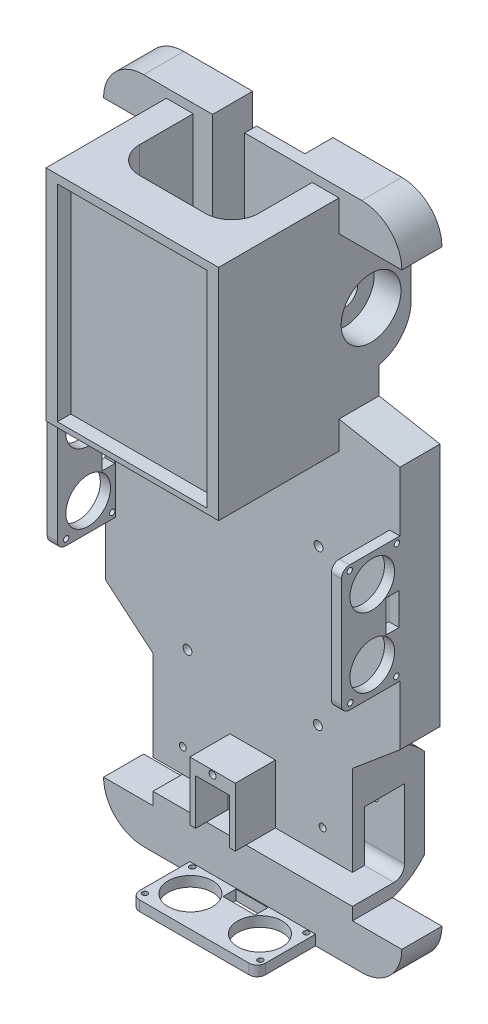
SolidWorks part; units mm, degrees
ref_plane "Alzado" through (0, 0, 0) normal (0, 0, 1) x (1, 0, 0)
ref_plane "Planta" through (0, 0, 0) normal (0, 1, 0) x (1, 0, 0)
ref_plane "Vista lateral" through (0, 0, 0) normal (1, 0, 0) x (0, 0, -1)
sketch "Croquis1" plane through (0, 0, 0) normal (0, 0, 1) x (1, 0, 0)
  line L0 (-55.75, 30) -> (-32.25, 30)
  line L1 (-32.25, 30) -> (-32.25, -30)
  line L2 (-32.25, -30) -> (-55, -34.2202)
  line L3 (-55, -34.2202) -> (-55, -125.7202)
  line L4 (-40.7501, 45) -> (0, 45)
  line L6 (-15, 15) -> (-15, -15)
  line L11 (-55, -125.7202) -> (-37.2737, -140.5944)
  line L12 (40.75, 45) -> (0, 45)
  line L17 (55, -125.7202) -> (37.2737, -140.5944)
  line L20 (15, 15) -> (15, -15)
  line L21 (-55, -79.9702) -> (55, -79.9702) construction
  line L22 (55, -34.2202) -> (55, -125.7202)
  line L23 (32.25, -30) -> (55, -34.2202)
  line L24 (32.25, 30) -> (32.25, -30)
  line L25 (55.75, 30) -> (32.25, 30)
  line L26 (-55.75, -189.9405) -> (-37.2737, -189.9405)
  line L27 (55.75, -189.9405) -> (37.2737, -189.9405)
  line L28 (40.75, -204.9405) -> (0, -204.9405)
  line L29 (-40.7501, -204.9405) -> (0, -204.9405)
  line L30 (-37.2737, -189.9405) -> (-37.2737, -140.5944)
  line L31 (37.2737, -189.9405) -> (37.2737, -140.5944)
  line L32 (-15, 15) -> (15, 15)
  line L33 (-15, -15) -> (15, -15)
  arc A4 (-55.75, 30) -> (-40.7501, 45) centre (-40.75, 30) cw
  arc A5 (55.75, 30) -> (40.75, 45) centre (40.75, 30) ccw
  arc A8 (55.75, -189.9405) -> (40.75, -204.9405) centre (40.75, -189.9405) cw
  arc A9 (-55.75, -189.9405) -> (-40.7501, -204.9405) centre (-40.75, -189.9405) ccw
  point P11 (0, 15)
  point P13 (-15, 0)
  point P20 (-32.25, 0)
  dimension "D10" = 15
  dimension "D22" = 15
  dimension "D1" = 60
  dimension "D3" = 55
  dimension "D4" = 23.5
  dimension "D5" = 91.5
  dimension "D6" = 23.1381
  dimension "D7" = 30
  dimension "D8" = 30
  dimension "D9" = 17.25
  dimension "D11" = 14.9999
  dimension "D12" = 15
  dimension "D13" = 23.14
  dimension "D14" = 18.4763
  dimension "D16" = 130
  dimension "D19" = 15
  dimension "D20" = 110
  dimension "D21" = 23.14
  dimension "D23" = 23.5
  dimension "D24" = 23.1381
extrude "Saliente-Extruir1" add sketch "Croquis1" along normal blind 15
sketch "Croquis6" plane through (-32.25, 0, 0) normal (-1, 0, 0) x (0, 0, 1)
  line L5 (0, 0) -> (5.215, 0) construction
  line L6 (0, 30) -> (0, -30) construction
  circle A0 centre (3, 0) radius 11.175
  circle A1 centre (3, 0) radius 5 construction
  circle A2 centre (3, 0) radius 25 construction
  dimension "D1" = 22.35
  dimension "D3" = 10
  dimension "D4" = 50
  dimension "D2" = 3
extrude "Cortar-Extruir1" cut sketch "Croquis6" against normal blind 10
sketch "Croquis11" plane through (0, 0, 0) normal (0, 0, -1) x (-1, 0, 0)
  line L0 (32.25, -10.7648) -> (32.25, -30) construction
  line L1 (15, 20) -> (32.25, 20)
  line L2 (15, 20) -> (15, -20)
  line L3 (15, -20) -> (32.25, -20)
  line L4 (32.25, 20) -> (32.25, -20)
  line L5 (15, 15) -> (15, -15) construction
  line L6 (55.75, 30) -> (32.25, 30) construction
  line L7 (0, -8.0419) -> (0, 11.3864) construction
  line L8 (-15, -20) -> (-32.25, -20)
  line L9 (-32.25, 20) -> (-32.25, -20)
  line L10 (-15, 20) -> (-32.25, 20)
  line L11 (-15, 20) -> (-15, -20)
  dimension "D1" = 10
  dimension "D2" = 10
extrude "Saliente-Extruir3" add sketch "Croquis11" along normal blind 12
sketch "Croquis9" plane through (-22.25, 0, 0) normal (-1, 0, 0) x (0, 0, 1)
  circle A0 centre (3, 0) radius 5
  arc A1 (0, -10.7648) -> (0, 10.7648) centre (3, 0) ccw construction
  dimension "D1" = 10
extrude "Cortar-Extruir2" cut sketch "Croquis9" against normal through all both and the other way through all
sketch "Croquis12" plane through (32.25, 0, 0) normal (1, 0, 0) x (0, 0, -1)
  line L2 (0, 0) -> (-9.4705, 0) construction
  line L5 (12, 20) -> (12, -20) construction
  line L6 (0, 20) -> (12, 20)
  line L7 (12, 20) -> (12, 5)
  line L8 (12, -20) -> (12, -5)
  line L9 (0, -20) -> (12, -20)
  arc A3 (12, 5) -> (0, 20) centre (-3.375, 5) ccw
  arc A4 (12, -5) -> (0, -20) centre (-3.375, -5) cw
  dimension "D1" = 15
sketch "Croquis14" plane through (0, 0, 15) normal (0, 0, 1) x (1, 0, 0)
  line L0 (-32.25, 30) -> (-32.25, -30) construction
  line L1 (32.25, 41.5932) -> (-32.25, 41.5932)
  line L2 (32.25, 41.5932) -> (32.25, -40.4068)
  line L3 (32.25, -40.4068) -> (-32.25, -40.4068)
  line L4 (-32.25, 41.5932) -> (-32.25, -40.4068)
  line L5 (32.25, -30) -> (32.25, 30) construction
  line L8 (40.75, 45) -> (-40.7501, 45) construction
  dimension "D1" = 3.4068
  dimension "D2" = 10.4068
extrude "Saliente-Extruir4" add sketch "Croquis14" along normal blind 40
sketch "Croquis10" plane through (32.25, 0, 0) normal (1, 0, 0) x (0, 0, -1)
  circle A0 centre (-3, 0) radius 11.175
  circle A1 centre (-3, 0) radius 5 construction
  arc A2 (0, 10.7648) -> (0, -10.7648) centre (-3, 0) ccw construction
extrude "Cortar-Extruir3" cut sketch "Croquis10" against normal blind 10
sketch "Croquis13" plane through (-32.25, 0, 0) normal (-1, 0, 0) x (0, 0, 1)
  circle A0 centre (3, 0) radius 11.175
  arc A1 (0, -10.7648) -> (0, 10.7648) centre (3, 0) ccw construction
extrude "Cortar-Extruir5" cut sketch "Croquis13" against normal blind 10 and the other way through all
sketch "Croquis15" plane through (0, -40.4068, 0) normal (0, -1, 0) x (1, 0, 0)
  line L0 (-22.25, 15) -> (-22.25, 35)
  line L1 (-32.25, 15) -> (32.25, 15) construction
  line L2 (-12.25, 45) -> (12.25, 45)
  line L3 (22.25, 35) -> (22.25, 15)
  line L4 (22.25, 15) -> (-22.25, 15)
  line L5 (-32.25, 55) -> (-32.25, 15) construction
  line L6 (32.25, 55) -> (32.25, 15) construction
  line L7 (-32.25, 55) -> (32.25, 55) construction
  arc A0 (22.25, 35) -> (12.25, 45) centre (12.25, 35) ccw
  arc A1 (-22.25, 35) -> (-12.25, 45) centre (-12.25, 35) cw
  dimension "D4" = 10
  dimension "D1" = 10
  dimension "D2" = 10
  dimension "D3" = 10
extrude "Cortar-Extruir6" cut sketch "Croquis15" against normal through all
sketch "Croquis16" plane through (0, 0, 55) normal (0, 0, 1) x (1, 0, 0)
  line L1 (-28, 38.5) -> (28, 38.5)
  line L2 (-28, 38.5) -> (-28, -38.5)
  line L3 (-28, -38.5) -> (28, -38.5)
  line L4 (28, 38.5) -> (28, -38.5)
  line L5 (-32.25, 41.5932) -> (32.25, 41.5932)
  line L6 (-32.25, 41.5932) -> (-32.25, -40.4068)
  line L7 (-32.25, -40.4068) -> (32.25, -40.4068)
  line L8 (32.25, 41.5932) -> (32.25, -40.4068)
  point P4 (0, 38.5)
  point P6 (28, 0)
  dimension "D1" = 77
  dimension "D2" = 56
extrude "Saliente-Extruir5" add sketch "Croquis16" along normal blind 5
sketch "Croquis17" plane through (0, 0, 15) normal (0, 0, 1) x (1, 0, 0)
  line L0 (15, 15) -> (15, 45)
  line L1 (15, 45) -> (-15, 45)
  line L2 (40.75, 45) -> (-40.7501, 45) construction
  line L3 (-15, 45) -> (-15, 15)
  line L4 (15, 15) -> (-15, 15) construction
  line L5 (15, 15) -> (-15, 15)
  line L6 (-15, 15) -> (-15, -15) construction
extrude "Cortar-Extruir7" cut sketch "Croquis17" against normal through all
sketch "Croquis19" plane through (0, -15, 0) normal (0, 1, 0) x (1, 0, 0)
  line L0 (-15, -15) -> (-15, 0) construction
  line L1 (15, -15) -> (-3, -15)
  line L2 (15, -15) -> (15, -10.5)
  line L3 (15, -10.5) -> (-3, -10.5)
  line L4 (-3, -15) -> (-3, -10.5)
  dimension "D1" = 12
  dimension "D2" = 2.5
extrude "Saliente-Extruir6" add sketch "Croquis19" along normal up to vertex (60 mm away)
sketch "Croquis22" plane through (0, -15, 0) normal (0, 1, 0) x (1, 0, 0)
  line L1 (-15, 0) -> (-3, 0)
  line L2 (-15, 0) -> (-15, -15)
  line L3 (-15, -15) -> (-3, -15)
  line L4 (-3, 0) -> (-3, -15)
extrude "Cortar-Extruir8" cut sketch "Croquis22" against normal blind 2
sketch "Croquis23" plane through (0, 0, 15) normal (0, 0, 1) x (1, 0, 0)
  line L1 (51.2, -56.4702) -> (55, -56.4702)
  line L2 (51.2, -56.4702) -> (51.2, -103.4702)
  line L3 (51.2, -103.4702) -> (55, -103.4702)
  line L4 (55, -56.4702) -> (55, -103.4702)
  line L6 (55, -125.7202) -> (55, -34.2202) construction
  line L7 (0, 0) -> (0, -130.3454) construction
  line L8 (-51.2, -103.4702) -> (-55, -103.4702)
  line L9 (-55, -56.4702) -> (-55, -103.4702)
  line L10 (-51.2, -56.4702) -> (-55, -56.4702)
  line L11 (-51.2, -56.4702) -> (-51.2, -103.4702)
  point P6 (55, -79.9702)
  point P7 (55, -79.9702)
  dimension "D1" = 3.8
  dimension "D2" = 47
extrude "Saliente-Extruir8" add sketch "Croquis23" along normal blind 19.8
sketch "Croquis24" plane through (55, 0, 0) normal (1, 0, 0) x (0, 0, -1)
  line L0 (-34.8, -103.4702) -> (-15, -103.4702) construction
  line L1 (-34.8, -103.4702) -> (-34.8, -56.4702) construction
  line L2 (-34.8, -102.4702) -> (-15, -102.4702) construction
  line L3 (-34.8, -102.4702) -> (-34.8, -57.4702) construction
  line L4 (-34.8, -57.4702) -> (-15, -57.4702) construction
  line L5 (-15, -102.4702) -> (-15, -57.4702) construction
  line L6 (-15, -125.7202) -> (-15, -103.4702) construction
  line L7 (-34.8, -56.4702) -> (-15, -56.4702) construction
  line L8 (-20.1, -85.9702) -> (-15.3, -85.9702)
  line L9 (-20.1, -85.9702) -> (-20.1, -73.9702)
  line L10 (-20.1, -73.9702) -> (-15.3, -73.9702)
  line L11 (-15.3, -85.9702) -> (-15.3, -73.9702)
  line L12 (-24.9, -56.4702) -> (-24.9, -58.3702) construction
  line L13 (-24.9, -103.4702) -> (-24.9, -101.771) construction
  circle A0 centre (-25.3, -66.9702) radius 8.35
  circle A1 centre (-25.3, -92.9702) radius 8.35
  circle A2 centre (-16.3, -101.2702) radius 1
  circle A3 centre (-33.7, -58.3702) radius 1
  circle A4 centre (-16.1, -58.3702) radius 1
  circle A5 centre (-33.5, -101.2702) radius 1
  point P16 (-20.1, -79.9702)
  point P20 (-34.8, -79.9702)
  point P21 (-34.8, -79.9702)
  dimension "D1" = 16.7
  dimension "D2" = 16.7
  dimension "D3" = 2
  dimension "D4" = 2.2
  dimension "D5" = 2
  dimension "D6" = 1.9
  dimension "D7" = 45
  dimension "D8" = 13
  dimension "D9" = 1.3
  dimension "D10" = 1.1
  dimension "D11" = 13
  dimension "D12" = 12
  dimension "D13" = 4.8
  dimension "D14" = 0.3
  dimension "D15" = 9.5
extrude "Cortar-Extruir10" cut sketch "Croquis24" against normal through all
sketch "Croquis25" plane through (0, 0, 34.8) normal (0, 0, 1) x (1, 0, 0)
  line L1 (-55, -56.4702) -> (-51.2, -56.4702)
  line L2 (-55, -56.4702) -> (-55, -103.4702)
  line L3 (-55, -103.4702) -> (-51.2, -103.4702)
  line L4 (-51.2, -56.4702) -> (-51.2, -103.4702)
  line L5 (51.2, -56.4702) -> (55, -56.4702)
  line L6 (51.2, -56.4702) -> (51.2, -103.4702)
  line L7 (51.2, -103.4702) -> (55, -103.4702)
  line L8 (55, -56.4702) -> (55, -103.4702)
extrude "Saliente-Extruir9" add sketch "Croquis25" along normal blind 2
fillet "Redondeo2" radius 3 4 edges at (53.1, -56.4702, 36.8) (53.1, -103.4702, 36.8) (-53.1, -56.4702, 36.8) (-53.1, -103.4702, 36.8)
sketch "Croquis26" plane through (0, 0, 15) normal (0, 0, 1) x (1, 0, 0)
  line L0 (-23.5001, -201.1405) -> (-23.5001, -204.9405)
  line L1 (-23.5001, -204.9405) -> (23.4999, -204.9405)
  line L2 (23.4999, -204.9405) -> (23.4999, -201.1405)
  line L3 (23.4999, -201.1405) -> (-23.5001, -201.1405)
  line L4 (-40.7501, -204.9405) -> (40.75, -204.9405) construction
  point P6 (-0.0001, -204.9405)
  point P7 (-0.0001, -204.9405)
  dimension "D1" = 3.8
  dimension "D2" = 47
extrude "Saliente-Extruir10" add sketch "Croquis26" along normal blind 21.8
fillet "Redondeo3" radius 3 2 edges at (23.4999, -203.0405, 36.8) (-23.5001, -203.0405, 36.8)
sketch "Croquis28" plane through (0, -204.9405, 0) normal (0, -1, 0) x (1, 0, 0)
  line L0 (-32.25, 15) -> (-22.25, 15) construction
  line L1 (-6, 20.1) -> (6, 20.1)
  line L2 (-6, 20.1) -> (-6, 15.3)
  line L3 (-6, 15.3) -> (6, 15.3)
  line L4 (6, 20.1) -> (6, 15.3)
  line L5 (-20.5001, 36.8) -> (20.4999, 36.8) construction
  line L6 (-23.5001, 33.8) -> (-23.5001, 15) construction
  line L8 (23.4999, 33.8) -> (23.4999, 15) construction
  line L9 (0, -0.6164) -> (0, 0) construction
  line L10 (0, 0) -> (0, -5.7529) construction
  circle A0 centre (-13, 25.3) radius 8.35
  circle A1 centre (13, 25.3) radius 8.35
  circle A2 centre (-21.3001, 16.3) radius 1
  circle A3 centre (21.5999, 33.7) radius 1
  circle A4 centre (21.3001, 16.3) radius 1
  circle A5 centre (-21.5999, 33.7) radius 1
  point P6 (0, 15.3)
  dimension "D4" = 16.7
  dimension "D7" = 16.7
  dimension "D9" = 2
  dimension "D12" = 2
  dimension "D1" = 0.3
  dimension "D2" = 12
  dimension "D3" = 4.8
  dimension "D5" = 13
  dimension "D6" = 13
  dimension "D8" = 11.5
  dimension "D10" = 2.2
  dimension "D11" = 1.3
  dimension "D13" = 1.9
  dimension "D14" = 3.1
extrude "Cortar-Extruir11" cut sketch "Croquis28" against normal blind 21.8
extrude "Cortar-Extruir12" cut sketch "Croquis12" against normal through all both and the other way through all
sketch "Croquis29" plane through (0, 0, 15) normal (0, 0, 1) x (1, 0, 0)
  line L2 (0, 0) -> (0, -45.8702) construction
  circle A0 centre (-24.3737, -132.9944) radius 1.65
  circle A1 centre (24.6263, -74.9944) radius 1.65
  circle A2 centre (-24.6263, -74.9944) radius 1.65
  circle A3 centre (24.3737, -132.9944) radius 1.65
  dimension "D1" = 3.3
  dimension "D3" = 12.9
  dimension "D4" = 3.3
  dimension "D2" = 7.6
  dimension "D5" = 58
  dimension "D6" = 49
extrude "Cortar-Extruir13" cut sketch "Croquis29" against normal through all both and the other way through all
sketch "Croquis32" plane through (0, 0, 0) normal (0, 0, -1) x (-1, 0, 0)
  line L0 (0, 0) -> (0, -47.6418) construction
  circle A0 centre (-24.6263, -74.9944) radius 5.15
  circle A1 centre (-24.6263, -74.9944) radius 1.65 construction
  circle A2 centre (-24.3737, -132.9944) radius 5.15
  circle A3 centre (-24.3737, -132.9944) radius 1.65 construction
  circle A4 centre (24.3737, -132.9944) radius 5.15
  circle A5 centre (24.6263, -74.9944) radius 5.15
  dimension "D1" = 3.5
  dimension "D2" = 3.5
extrude "Cortar-Extruir14" cut sketch "Croquis32" against normal blind 8 and the other way through all
sketch "Croquis34" plane through (0, 0, 0) normal (0, 0, -1) x (-1, 0, 0)
  line L0 (-37.2737, -189.9405) -> (-37.2737, -140.5944) construction
  line L1 (-37.2737, -140.5944) -> (-15, -140.5944)
  line L2 (-37.2737, -140.5944) -> (-37.2737, -189.9405)
  line L3 (-37.2737, -189.9405) -> (-15, -189.9405)
  line L4 (-15, -140.5944) -> (-15, -189.9405)
  line L5 (-15, 45) -> (-15, 20) construction
  line L6 (15, -140.5944) -> (37.2737, -140.5944)
  line L7 (15, -140.5944) -> (15, -189.9405)
  line L8 (15, -189.9405) -> (37.2737, -189.9405)
  line L9 (37.2737, -140.5944) -> (37.2737, -189.9405)
  line L10 (37.2737, -140.5944) -> (37.2737, -189.9405) construction
  line L11 (15, 20) -> (15, 45) construction
extrude "Saliente-Extruir11" add sketch "Croquis34" along normal blind 12
sketch "Croquis35" plane through (37.2737, 0, 0) normal (1, 0, 0) x (0, 0, -1)
  line L0 (0, -140.5944) -> (12, -140.5944)
  line L1 (12, -140.5944) -> (12, -148.5944)
  line L3 (0, -189.9405) -> (12, -189.9405)
  line L4 (12, -189.9405) -> (12, -181.9405)
  line L5 (12, -140.5944) -> (12, -189.9405) construction
  arc A3 (0, -189.9405) -> (12, -181.9405) centre (-7.782, -165.2674) ccw
  arc A4 (12, -148.5944) -> (0, -140.5944) centre (-7.782, -165.2674) ccw
  dimension "D1" = 8
extrude "Cortar-Extruir17" cut sketch "Croquis35" against normal through all both and the other way through all
sketch "Croquis37" plane through (-37.2737, 0, 0) normal (-1, 0, 0) x (0, 0, 1)
  line L0 (-12, -181.9405) -> (-12, -148.5944) construction
  line L1 (0, -140.5944) -> (0, -189.9405) construction
  line L7 (-4.5, -155.2674) -> (10.5, -155.2674)
  line L8 (-4.5, -155.2674) -> (-4.5, -181.2674)
  line L9 (-0.5, -185.2674) -> (6.5, -185.2674)
  line L10 (10.5, -155.2674) -> (10.5, -181.2674)
  circle A0 centre (3, -165.2674) radius 5.5 construction
  arc A1 (6.5, -185.2674) -> (10.5, -181.2674) centre (6.5, -181.2674) ccw
  arc A2 (-0.5, -185.2674) -> (-4.5, -181.2674) centre (-0.5, -181.2674) cw
  point P5 (-12, -165.2674)
  point P14 (3, -185.2674)
  point P16 (10.5, -185.2674)
  point P19 (-4.5, -185.2674)
  dimension "D1" = 11
  dimension "D4" = 30
  dimension "D6" = 4
  dimension "D2" = 3
  dimension "D3" = 10
  dimension "D5" = 15
extrude "Cortar-Extruir18" cut sketch "Croquis37" against normal through all both and the other way through all
sketch "Croquis38" plane through (0, 0, -12) normal (0, 0, -1) x (-1, 0, 0)
  line L0 (-37.2737, -148.5944) -> (-37.2737, -181.9405) construction
  line L1 (-15, -148.5944) -> (-37.2737, -148.5944) construction
  line L2 (0, 0) -> (0, -210.3255) construction
  circle A0 centre (-26.1369, -165.2674) radius 1.3
  circle A1 centre (26.1369, -165.2674) radius 1.3
  point P5 (-37.2737, -165.2674)
  point P9 (-26.1369, -148.5944)
  dimension "D1" = 2.6
extrude "Cortar-Extruir19" cut sketch "Croquis38" against normal through all both and the other way through all
sketch "Croquis39" plane through (0, 0, 15) normal (0, 0, 1) x (1, 0, 0)
  line L0 (37.2737, -189.9405) -> (37.2737, -140.5944) construction
  line L1 (-37.2737, -185.2674) -> (37.2737, -185.2674)
  line L2 (-37.2737, -185.2674) -> (-37.2737, -174.2674)
  line L3 (-37.2737, -174.2674) -> (37.2737, -174.2674)
  line L4 (37.2737, -185.2674) -> (37.2737, -174.2674)
  line L5 (-37.2737, -140.5944) -> (-37.2737, -189.9405) construction
  dimension "D1" = 11
extrude "Cortar-Extruir20" cut sketch "Croquis39" against normal up to vertex and the other way through all
sketch "Croquis40" plane through (0, 0, 15) normal (0, 0, 1) x (1, 0, 0)
  line L0 (-37.2737, -174.2674) -> (37.2737, -174.2674) construction
  line L1 (-8.5, -174.2674) -> (8.5, -174.2674)
  line L2 (-8.5, -174.2674) -> (-8.5, -152.2674)
  line L3 (-8.5, -152.2674) -> (8.5, -152.2674)
  line L4 (8.5, -174.2674) -> (8.5, -152.2674)
  point P6 (0, -174.2674)
  dimension "D1" = 22
  dimension "D2" = 17
extrude "Saliente-Extruir12" add sketch "Croquis40" along normal blind 15
sketch "Croquis41" plane through (0, 0, 30) normal (0, 0, 1) x (1, 0, 0)
  line L1 (8.5, -152.2674) -> (-8.5, -152.2674) construction
  circle A0 centre (0, -153.7674) radius 1.3
  dimension "D1" = 2.6
  dimension "D2" = 1.5
extrude "Cortar-Extruir25" cut sketch "Croquis41" against normal blind 15
sketch "Croquis42" plane through (0, 0, 30) normal (0, 0, 1) x (1, 0, 0)
  line L2 (-6.3, -157.2674) -> (6.3, -157.2674)
  line L3 (-6.3, -157.2674) -> (-6.3, -164.2674)
  line L4 (-6.3, -164.2674) -> (6.3, -164.2674)
  line L5 (6.3, -157.2674) -> (6.3, -164.2674)
  circle A0 centre (0, -153.7674) radius 1.3 construction
  point P0 (0, -157.2674)
  dimension "D1" = 12.6
  dimension "D2" = 3.5
  dimension "D3" = 7
extrude "Cortar-Extruir26" cut sketch "Croquis42" against normal blind 7.1
sketch "Croquis43" plane through (0, 0, 30) normal (0, 0, 1) x (1, 0, 0)
  line L0 (-8.5, -174.2674) -> (8.5, -174.2674) construction
  line L1 (-6.3, -164.2674) -> (6.3, -164.2674)
  line L2 (-6.3, -164.2674) -> (-6.3, -174.2674)
  line L3 (-6.3, -174.2674) -> (6.3, -174.2674)
  line L4 (6.3, -164.2674) -> (6.3, -174.2674)
  line L5 (6.3, -164.2674) -> (6.3, -157.2674) construction
extrude "Cortar-Extruir27" cut sketch "Croquis43" against normal blind 12.1
